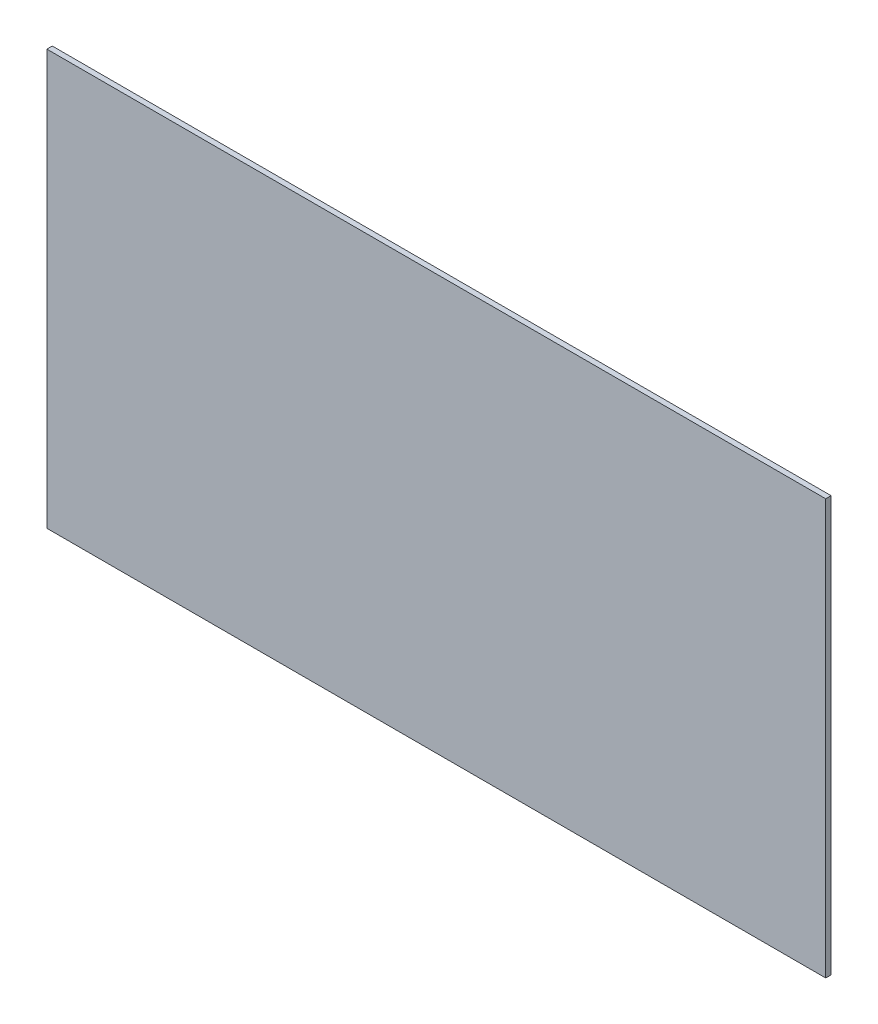
SolidWorks part; units mm, degrees
material "Maple"
ref_plane "Front Plane" through (0, 0, 0) normal (0, 0, 1) x (1, 0, 0)
ref_plane "Top Plane" through (0, 0, 0) normal (0, 1, 0) x (1, 0, 0)
ref_plane "Right Plane" through (0, 0, 0) normal (1, 0, 0) x (0, 0, -1)
sketch "Sketch1" plane through (0, 0, 0) normal (0, 0, 1) x (1, 0, 0)
  line L1 (0, 0) -> (1835.15, 0)
  line L2 (0, 0) -> (0, 977.9)
  line L3 (0, 977.9) -> (1835.15, 977.9)
  line L4 (1835.15, 0) -> (1835.15, 977.9)
  dimension "D1" = 1835.15
  dimension "D2" = 977.9
extrude "Boss-Extrude1" add sketch "Sketch1" along normal blind 12.7 contours L2 L3 L4 L1
